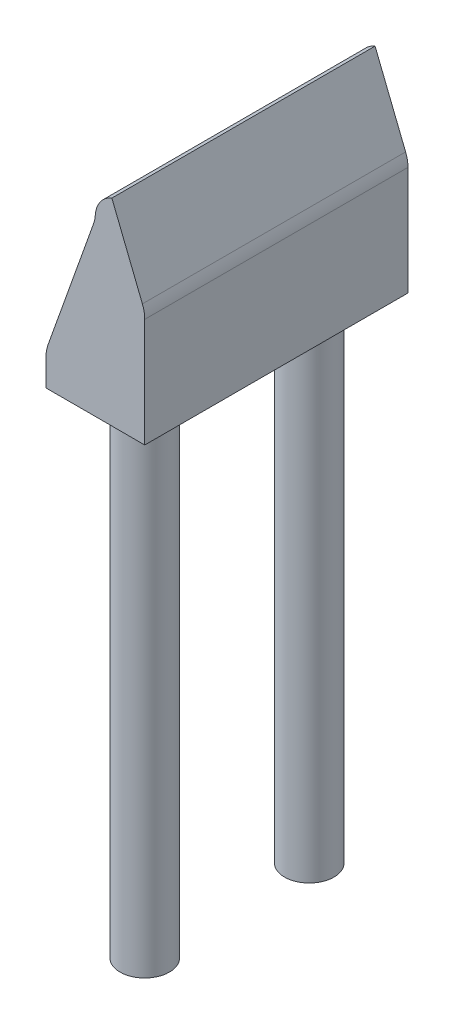
SolidWorks part; units mm, degrees
ref_plane "Front Plane" through (0, 0, 0) normal (0, 0, 1) x (1, 0, 0)
ref_plane "Top Plane" through (0, 0, 0) normal (0, 1, 0) x (1, 0, 0)
ref_plane "Right Plane" through (0, 0, 0) normal (1, 0, 0) x (0, 0, -1)
sketch "Sketch1" plane through (0, 0, 0) normal (0, 1, 0) x (1, 0, 0)
  line L1 (0, 0) -> (-30, 0)
  line L2 (0, 0) -> (0, 80)
  line L3 (0, 80) -> (-30, 80)
  line L4 (-30, 0) -> (-30, 80)
  dimension "D1" = 80
  dimension "D2" = 30
extrude "Boss-Extrude1" add sketch "Sketch1" along normal blind 10
sketch "Sketch2" plane through (0, 0, -80) normal (0, 0, -1) x (-1, 0, 0)
  line L0 (0, 10) -> (0, 35)
  line L1 (0, 35) -> (10, 60)
  line L2 (15.0084, 52) -> (30, 10)
  line L4 (0, 10) -> (0, 0) construction
  line L9 (0, 0) -> (30, 0)
  line L10 (30, 0) -> (30, 10)
  line L11 (30, 10) -> (0, 10)
  line L12 (0, 10) -> (0, 0)
  line L13 (0, 0) -> (30, 0)
  line L14 (30, 0) -> (30, 10)
  line L16 (0, 10) -> (0, 0)
  arc A0 (10, 60) -> (15.0084, 52) centre (7.0289, 52.5722) cw
  point P7 (14.3582, 52.4837)
  point P10 (9.0949, 60)
  dimension "D1" = 8
  dimension "D2" = 25
  dimension "D3" = 25
  dimension "D4" = 42
  dimension "D5" = 10
  dimension "D6" = 0
extrude "Boss-Extrude2" add sketch "Sketch2" against normal blind 80
fillet "Fillet1" radius 10 1 edges at (0, 35, -40)
fillet "Fillet2" radius 10 1 edges at (-15.0084, 52, -40)
fillet "Fillet4" radius 10 1 edges at (-30, 10, -40)
sketch "Sketch3" plane through (0, 0, 0) normal (0, -1, 0) x (1, 0, 0)
  line L0 (-30, -80) -> (-30, 0) construction
  line L1 (-30, 0) -> (0, 0) construction
  line L2 (0, -80) -> (-30, -80) construction
  circle A0 centre (-15, -15) radius 7.5
  circle A1 centre (-15, -65) radius 7.5
  point P8 (-8.4278, -10.5916)
  dimension "D1" = 15
  dimension "D2" = 15
  dimension "D3" = 15
  dimension "D4" = 15
  dimension "D5" = 15
  dimension "D6" = 15
extrude "Boss-Extrude3" add sketch "Sketch3" along normal blind 150
